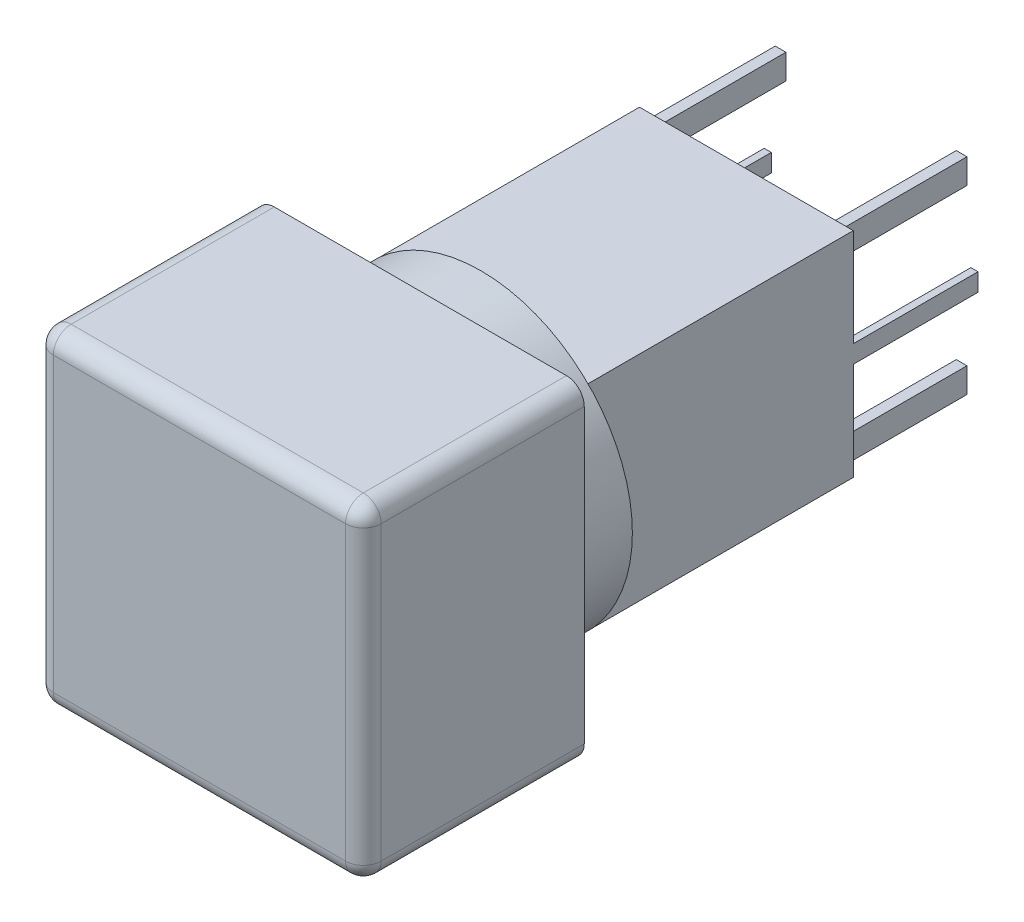
SolidWorks part; units mm, degrees
ref_plane "Спереди" through (0, 0, 0) normal (0, 0, 1) x (1, 0, 0)
ref_plane "Сверху" through (0, 0, 0) normal (0, 1, 0) x (1, 0, 0)
ref_plane "Справа" through (0, 0, 0) normal (1, 0, 0) x (0, 0, -1)
other "Configuration Table"
sketch "Эскиз1" plane through (0, 0, 0) normal (0, 0, 1) x (1, 0, 0)
  line L1 (-4.6, -4.6) -> (4.6, -4.6)
  line L2 (-4.6, -4.6) -> (-4.6, 4.6)
  line L3 (-4.6, 4.6) -> (4.6, 4.6)
  line L4 (4.6, -4.6) -> (4.6, 4.6)
  line L5 (-4.6, -4.6) -> (4.6, 4.6) construction
  line L6 (-4.6, 4.6) -> (4.6, -4.6) construction
  point P0 (0, 0)
  dimension "D1" = 9.2
extrude "Бобышка-Вытянуть1" add sketch "Эскиз1" along normal blind 6.2
fillet "Скругление1" radius 0.5 8 edges at (-4.6, -4.6, 3.1) (4.6, -4.6, 3.1) (4.6, 4.6, 3.1) (-4.6, 4.6, 3.1) (-4.6, 0, 6.2) (0, 4.6, 6.2) (4.6, 0, 6.2) (0, -4.6, 6.2)
sketch "Эскиз2" plane through (0, 0, 0) normal (0, 0, -1) x (-1, 0, 0)
  circle A0 centre (0, 0) radius 4.25
  dimension "D1" = 8.5
extrude "Бобышка-Вытянуть2" add sketch "Эскиз2" along normal blind 1.7
sketch "Эскиз3" plane through (0, 0, -1.7) normal (0, 0, -1) x (-1, 0, 0)
  line L1 (-3, -3) -> (3, -3)
  line L2 (-3, -3) -> (-3, 3)
  line L3 (-3, 3) -> (3, 3)
  line L4 (3, -3) -> (3, 3)
  line L5 (-3, -3) -> (3, 3) construction
  line L6 (-3, 3) -> (3, -3) construction
  point P0 (0, 0)
  dimension "D1" = 6
extrude "Бобышка-Вытянуть3" add sketch "Эскиз3" along normal blind 7.45
sketch "Эскиз4" plane through (0, 0, -9.15) normal (0, 0, -1) x (-1, 0, 0)
  line L0 (0, 0) -> (0, 2.54) construction
  line L1 (-2.54, -2.54) -> (2.54, -2.54) construction
  line L2 (-2.54, -2.54) -> (-2.54, 2.54) construction
  line L3 (-2.54, 2.54) -> (2.54, 2.54) construction
  line L4 (2.54, -2.54) -> (2.54, 2.54) construction
  line L5 (-2.54, -2.54) -> (2.54, 2.54) construction
  line L6 (-2.54, 2.54) -> (2.54, -2.54) construction
  line L7 (-2.69, 2.89) -> (-2.39, 2.89)
  line L8 (-2.69, 2.89) -> (-2.69, 2.19)
  line L9 (-2.69, 2.19) -> (-2.39, 2.19)
  line L10 (-2.39, 2.89) -> (-2.39, 2.19)
  line L11 (-2.69, 2.89) -> (-2.39, 2.19) construction
  line L12 (-2.69, 2.19) -> (-2.39, 2.89) construction
  line L13 (0, 0) -> (-2.54, 0) construction
  line L14 (2.69, 2.19) -> (2.39, 2.19)
  line L15 (2.69, 2.89) -> (2.69, 2.19)
  line L16 (2.69, 2.89) -> (2.39, 2.89)
  line L17 (2.39, 2.89) -> (2.39, 2.19)
  line L18 (2.69, -2.19) -> (2.39, -2.19)
  line L19 (2.69, -2.89) -> (2.39, -2.89)
  line L20 (2.69, -2.89) -> (2.69, -2.19)
  line L21 (2.39, -2.89) -> (2.39, -2.19)
  line L22 (-2.69, -2.19) -> (-2.39, -2.19)
  line L23 (-2.39, -2.89) -> (-2.39, -2.19)
  line L24 (-2.69, -2.89) -> (-2.39, -2.89)
  line L25 (-2.69, -2.89) -> (-2.69, -2.19)
  line L26 (-2.9, 0) -> (2.9, 0) construction
  line L27 (3, -0.25) -> (2.8, -0.25)
  line L28 (-3, -0.25) -> (-2.8, -0.25)
  line L29 (-3, -0.25) -> (-3, 0.25)
  line L30 (-3, 0.25) -> (-2.8, 0.25)
  line L31 (-2.8, -0.25) -> (-2.8, 0.25)
  line L32 (-3, -0.25) -> (-2.8, 0.25) construction
  line L33 (-3, 0.25) -> (-2.8, -0.25) construction
  line L34 (2.8, -0.25) -> (2.8, 0.25)
  line L35 (3, 0.25) -> (2.8, 0.25)
  line L36 (3, -0.25) -> (3, 0.25)
  point P0 (0, 0)
  point P28 (0, 0)
  dimension "D1" = 0.7
  dimension "D2" = 0.3
  dimension "D3" = 5.08
  dimension "D4" = 5.8
  dimension "D5" = 0.5
  dimension "D6" = 0.2
extrude "Бобышка-Вытянуть4" add sketch "Эскиз4" along normal blind 3.5
